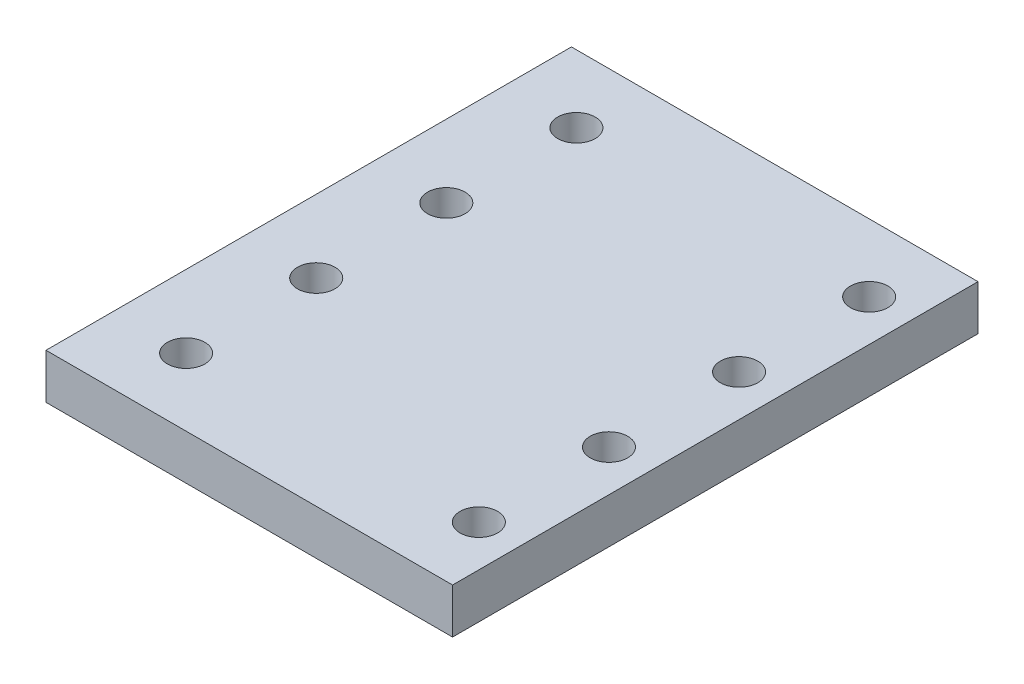
SolidWorks part; units mm, degrees
ref_plane "Спереди" through (0, 0, 0) normal (0, 0, 1) x (1, 0, 0)
ref_plane "Сверху" through (0, 0, 0) normal (0, 1, 0) x (1, 0, 0)
ref_plane "Справа" through (0, 0, 0) normal (1, 0, 0) x (0, 0, -1)
sketch "Эскиз1" plane through (0, 0, 0) normal (0, 1, 0) x (1, 0, 0)
  line L0 (16.2069, -21.8628) -> (-16.2931, -21.8628)
  line L1 (16.2069, -21.8628) -> (16.2069, 20.1372)
  line L2 (16.2069, 20.1372) -> (-16.2931, 20.1372)
  line L3 (-16.2931, -21.8628) -> (-16.2931, 20.1372)
  circle A0 centre (12.9069, 14.7372) radius 1.5
  circle A1 centre (12.9069, 4.3372) radius 1.5
  circle A2 centre (12.9069, -6.0628) radius 1.5
  circle A3 centre (12.9069, -16.4628) radius 1.5
  circle A4 centre (-10.4931, 14.7372) radius 1.5
  circle A5 centre (-10.4931, 4.3372) radius 1.5
  circle A6 centre (-10.4931, -16.4628) radius 1.5
  circle A7 centre (-10.4931, -6.0628) radius 1.5
extrude "Бобышка-Вытянуть1" add sketch "Эскиз1" along normal up to vertex (3.6065 mm away)
